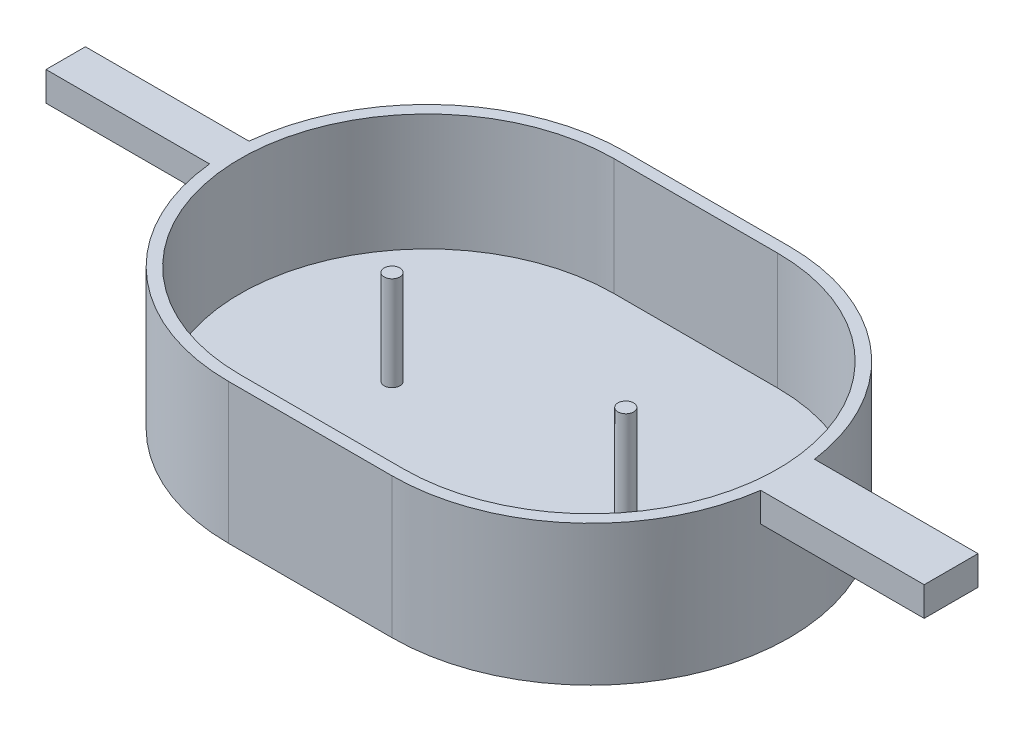
SolidWorks part; units mm, degrees
ref_plane "Front Plane" through (0, 0, 0) normal (0, 0, 1) x (1, 0, 0)
ref_plane "Top Plane" through (0, 0, 0) normal (0, 1, 0) x (1, 0, 0)
ref_plane "Right Plane" through (0, 0, 0) normal (1, 0, 0) x (0, 0, -1)
sketch "Sketch1" plane through (0, 0, 0) normal (0, 1, 0) x (1, 0, 0)
  line L0 (0, 0) -> (35.56, 0) construction
  line L1 (0, 40.64) -> (35.56, 40.64)
  line L2 (0, -40.64) -> (35.56, -40.64)
  line L3 (0, 0) -> (35.56, 0) construction
  line L4 (0, 43.18) -> (35.56, 43.18)
  line L5 (0, -43.18) -> (35.56, -43.18)
  arc A0 (0, 40.64) -> (0, -40.64) centre (0, 0) ccw
  arc A1 (35.56, -40.64) -> (35.56, 40.64) centre (35.56, 0) ccw
  arc A2 (0, 43.18) -> (0, -43.18) centre (0, 0) ccw
  arc A3 (35.56, -43.18) -> (35.56, 43.18) centre (35.56, 0) ccw
  point P3 (17.78, 0)
  point P8 (-40.64, 0)
  point P9 (76.2, 0)
  point P12 (17.78, 0)
  point P17 (0, 0)
  point P18 (-43.18, 0)
  point P19 (78.74, 0)
  dimension "D1" = 40.64
  dimension "D3" = 116.84
  dimension "D2" = 121.92
extrude "Boss-Extrude1" add sketch "Sketch1" along normal blind 25.4
sketch "Sketch3" plane through (0, 25.4, 0) normal (0, 1, 0) x (1, 0, 0)
  line L0 (0, 0) -> (35.56, 0) construction
  line L1 (0, 43.18) -> (35.56, 43.18)
  line L2 (0, -43.18) -> (35.56, -43.18)
  line L3 (35.56, 43.18) -> (0, 43.18) construction
  arc A0 (0, 43.18) -> (0, -43.18) centre (0, 0) ccw
  arc A1 (35.56, -43.18) -> (35.56, 43.18) centre (35.56, 0) ccw
  point P3 (17.78, 0)
  point P8 (78.74, 0)
  point P9 (-43.18, 0)
  dimension "D1" = 121.92
  dimension "D2" = 0
extrude "Boss-Extrude2" add sketch "Sketch3" against normal blind 5.08 from offset 25.4 offset against normal yes
sketch "Sketch4" plane through (0, 0, 0) normal (0, 1, 0) x (1, 0, 0)
  line L0 (0, 0) -> (35.56, 0) construction
  line L1 (0, 39.37) -> (35.56, 39.37) construction
  line L2 (0, -39.37) -> (35.56, -39.37) construction
  line L3 (35.56, 40.64) -> (0, 40.64) construction
  arc A0 (0, 39.37) -> (0, -39.37) centre (0, 0) ccw construction
  arc A1 (35.56, -39.37) -> (35.56, 39.37) centre (35.56, 0) ccw construction
  arc A2 (0, 40.64) -> (0, -40.64) centre (0, 0) ccw construction
  circle A3 centre (43.18, 0) radius 1.7018
  circle A4 centre (-7.62, 0) radius 1.7018
  point P3 (17.78, 0)
  point P8 (-39.37, 0)
  point P9 (74.93, 0)
  point P13 (-40.64, 0)
  point P14 (0, 0)
  point P15 (0, 0)
  point P19 (17.78, 40.64)
  point P23 (-13.8665, 0)
  point P24 (43.18, 0)
  point P25 (0, 0)
  dimension "D3" = 3.4036
  dimension "D5" = 3.4036
  dimension "D1" = 114.3
  dimension "D2" = 31.75
  dimension "D4" = 31.75
extrude "Boss-Extrude3" add sketch "Sketch4" along normal blind 20.4964
sketch "Sketch5" plane through (0, 25.4, 0) normal (0, 1, 0) x (1, 0, 0)
  line L0 (-40.4164, 4.2575) -> (-78.5164, 4.2575)
  line L1 (75.7771, 5.8474) -> (113.8771, 5.8474)
  line L3 (75.7771, -5.8474) -> (113.8771, -5.8474)
  line L4 (113.8771, 5.8474) -> (113.8771, -5.8474)
  line L5 (-40.4111, -4.3076) -> (-78.5164, -4.3076)
  line L6 (-78.5164, 4.2575) -> (-78.5164, -4.3076)
  arc A0 (35.56, -40.64) -> (35.56, 40.64) centre (35.56, 0) ccw construction
  arc A2 (35.56, -40.64) -> (35.56, 40.64) centre (35.56, 0) ccw construction
  arc A4 (0, 40.64) -> (0, -40.64) centre (0, 0) ccw construction
  arc A5 (-40.4164, 4.2575) -> (-40.4111, -4.3076) centre (0, 0) ccw
  arc A6 (75.7771, 5.8474) -> (75.7771, -5.8474) centre (35.56, 0) cw
  dimension "D1" = 38.1
  dimension "D2" = 38.1
extrude "Boss-Extrude4" add sketch "Sketch5" against normal blind 6.35
equation "\"D4@Sketch4\"=\"D2@Sketch4\""
equation "\"D5@Sketch4\"=\"D3@Sketch4\""
